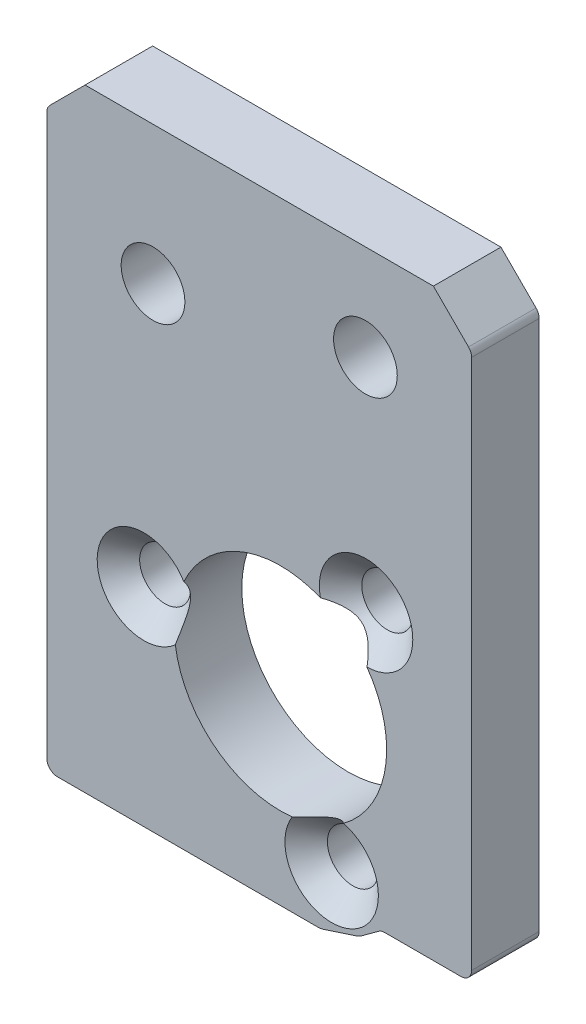
SolidWorks part; units mm, degrees
ref_plane "Front Plane" through (0, 0, 0) normal (0, 0, 1) x (1, 0, 0)
ref_plane "Top Plane" through (0, 0, 0) normal (0, 1, 0) x (1, 0, 0)
ref_plane "Right Plane" through (0, 0, 0) normal (1, 0, 0) x (0, 0, -1)
sketch "Sketch1" plane through (0, 0, 0) normal (0, 0, 1) x (1, 0, 0)
  line L1 (0, 0) -> (20, 0)
  line L2 (0, 0) -> (0, 29.11)
  line L3 (0, 29.11) -> (20, 29.11)
  line L4 (20, 0) -> (20, 29.11)
  circle A0 centre (5, 22.61) radius 1.5
  circle A1 centre (15, 24.61) radius 1.5
  arc A2 (15.0728, 12.0104) -> (12.8801, 13.743) centre (15.03, 14.21) ccw
  arc A3 (6.4499, 11.1828) -> (6.049, 8.4114) centre (4.57, 10.04) ccw
  arc A4 (11.5537, 4.1408) -> (13.9699, 5.0876) centre (13.41, 2.96) ccw
  circle A7 centre (15.03, 14.21) radius 1.2
  circle A8 centre (4.57, 10.04) radius 1.2
  circle A9 centre (13.41, 2.96) radius 1.2
  circle A10 centre (11, 9.11) radius 5
extrude "Boss-Extrude2" add sketch "Sketch1" against normal blind 3.18 contours A0 | A1 | L2 L1 L4 L3 | A7 | A10 | A8 | A9
hole_wizard "CSK for M2 Flat Head Machine Screw1" positions "Sketch10" profile "Sketch11" countersink size "M2" standard "ANSI Metric"
sketch "Sketch10" plane through (0, 0, 0) normal (0, 0, 1) x (1, 0, 0)
  point P0 (4.57, 10.04)
  point P3 (15.03, 14.21)
  point P6 (13.41, 2.96)
sketch "Sketch11" plane through (4.57, 10.04, 0) normal (1, 0, 0) x (0, -1, 0)
  line L0 (0, 0) -> (0, 4.23)
  line L1 (0, 4.23) -> (1.2, 3.509)
  line L2 (1.2, 3.509) -> (1.2, 1)
  line L3 (1.2, 1) -> (2.2, 0)
  line L5 (2.2, 0) -> (0, 0)
  line L6 (-1.2, 1) -> (-2.2, 0) construction
  line L10 (0, 4.23) -> (-1.2, 3.509) construction
  line L11 (0, -6.35) -> (0, 107.95) construction
  dimension "Hole Dia." = 2.4
  dimension "Hole Depth" = 4.23
  dimension "Near C'Sink Dia." = 4.4
  dimension "Near C'Sink Angle" = 90
  dimension "Drill Angle" = 118
chamfer "Chamfer1" distance 1.8 angle 45 2 edges at (0, 29.11, -1.59) (20, 29.11, -1.59)
fillet "Fillet1" radius 0.5 2 edges at (20, 27.31, -1.59) (0, 27.31, -1.59)
sketch "Sketch12" plane through (0, 0, -3.18) normal (0, 0, -1) x (-1, 0, 0)
  line L0 (0, 0) -> (-20, 0)
  line L1 (0, 0) -> (-20, 0) construction
  line L2 (-20, 0) -> (-20, 1.6068)
  line L3 (-20, 0) -> (-20, 27.1029) construction
  line L4 (-20, 1.6068) -> (-15.7486, 1.6068)
  line L6 (0, 0) -> (-20, 0) construction
  line L8 (0, 0.2514) -> (-13.8989, 0.2514)
  line L9 (-13.8989, 0.2514) -> (-15.7486, 1.6068)
  line L10 (0, 0) -> (0, 27.1029) construction
  line L11 (0, 0.2514) -> (0, 0)
extrude "Cut-Extrude1" cut sketch "Sketch12" against normal blind 4
fillet "Fillet6" radius 0.5 3 edges at (0, 0.2514, -1.59) (15.7486, 1.6068, -1.59) (20, 1.6068, -1.59)
sketch "Sketch14" plane through (0, 0, 0) normal (0, 0, 1) x (1, 0, 0)
  line L0 (12.8989, 0.2514) -> (13.8989, 0.2514)
  line L1 (13.8989, 0.2514) -> (0.5, 0.2514) construction
  line L2 (13.8989, 0.2514) -> (14.7055, 0.8424)
  line L3 (15.6166, 1.5101) -> (13.8989, 0.2514) construction
  line L4 (14.7055, 0.8424) -> (12.8989, 0.2514)
extrude "Cut-Extrude2" cut sketch "Sketch14" against normal blind 4
fillet "Fillet8" radius 1 2 edges at (12.8989, 0.2514, -1.59) (14.7055, 0.8424, -1.59)
